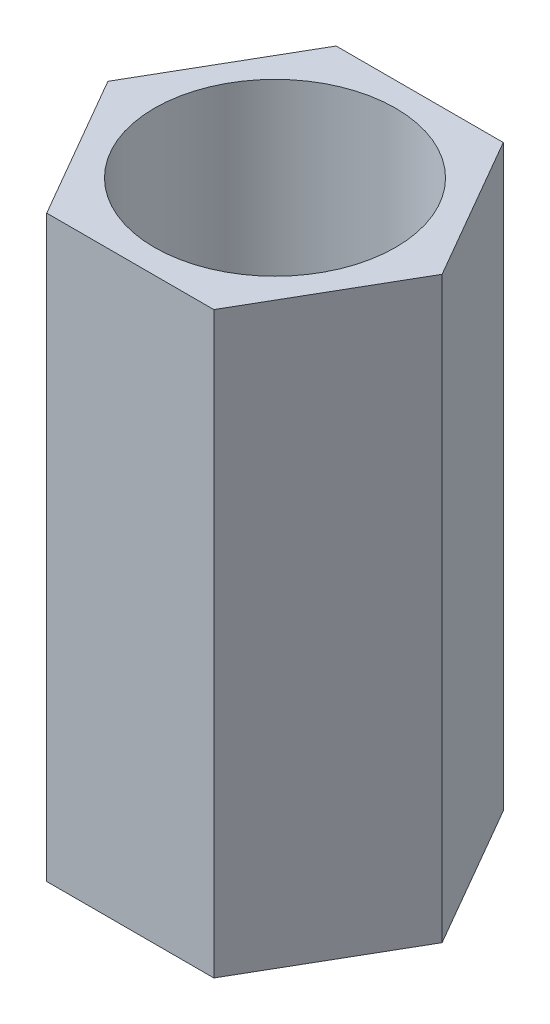
SolidWorks part; units mm, degrees
ref_plane "Front Plane" through (0, 0, 0) normal (0, 0, 1) x (1, 0, 0)
ref_plane "Top Plane" through (0, 0, 0) normal (0, 1, 0) x (1, 0, 0)
ref_plane "Right Plane" through (0, 0, 0) normal (1, 0, 0) x (0, 0, -1)
sketch "Sketch1" plane through (0, 0, 0) normal (0, 1, 0) x (1, 0, 0)
  line L1 (0.866, -1.5) -> (1.7321, 0)
  line L2 (1.7321, 0) -> (0.866, 1.5)
  line L3 (0.866, 1.5) -> (-0.866, 1.5)
  line L4 (-0.866, 1.5) -> (-1.7321, 0)
  line L5 (-1.7321, 0) -> (-0.866, -1.5)
  line L6 (-0.866, -1.5) -> (0.866, -1.5)
  circle A0 centre (0, 0) radius 1.25
  circle A1 centre (0, 0) radius 1.5 construction
  dimension "D1" = 2.5
  dimension "D2" = 3
extrude "Boss-Extrude1" add sketch "Sketch1" along normal blind 6
